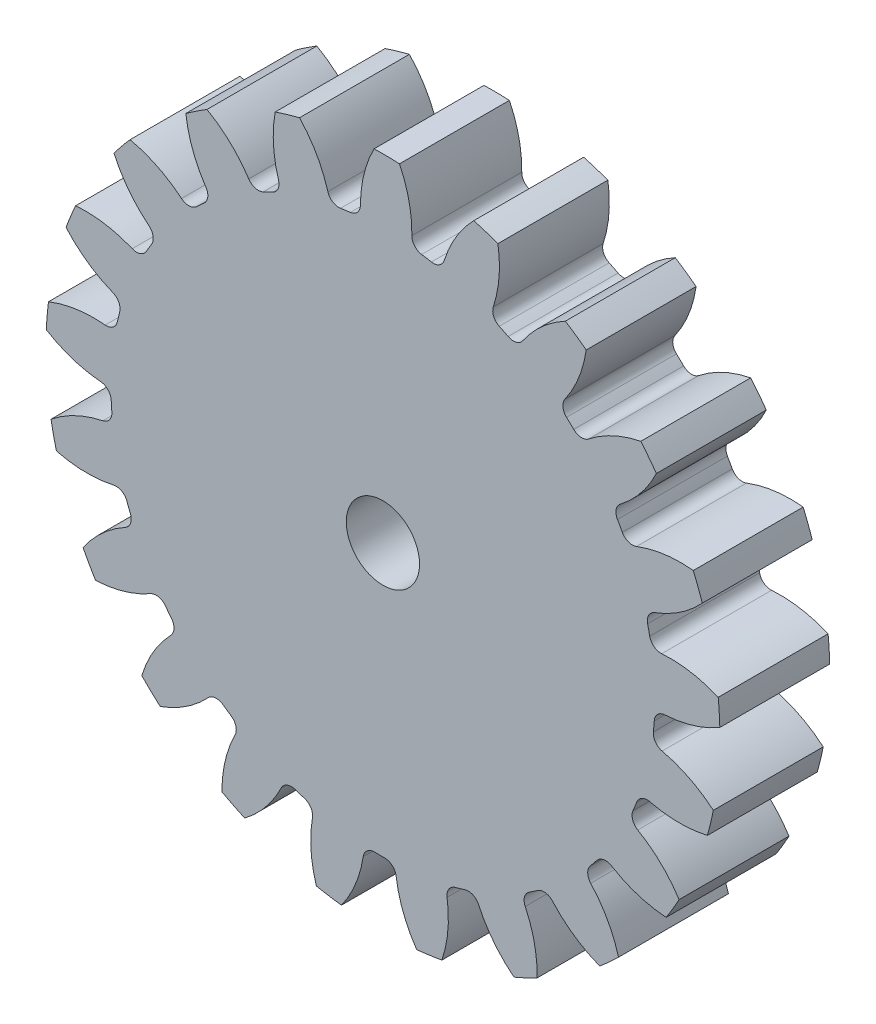
SolidWorks part; units mm, degrees
ref_plane "Front" through (0, 0, 0) normal (0, 0, 1) x (1, 0, 0)
ref_plane "Top" through (0, 0, 0) normal (0, 1, 0) x (1, 0, 0)
ref_plane "Right" through (0, 0, 0) normal (1, 0, 0) x (0, 0, -1)
sketch "Sketch3" plane through (0, 0, 0) normal (0, 0, 1) x (1, 0, 0)
  circle A0 centre (0, 0) radius 29.21
  dimension "od" = 58.42
extrude "gearBody" add sketch "Sketch3" along normal blind 9.525
sketch "Sketch2" plane through (0, 0, 0) normal (0, 0, 1) x (1, 0, 0)
  line L0 (0, 0) -> (23.855, 9.8811) construction
  line L1 (31.4408, -9.4565) -> (0, 0) construction
  line L2 (0, 0) -> (36.3143, 0) construction
  line L3 (26.6681, -0.3206) -> (26.3271, -4.2627) construction
  line L5 (26.4976, -2.2916) -> (0, 0) construction
  line L7 (0, 0) -> (25.8205, 0) construction
  arc A0 (25.8153, -0.5182) -> (25.521, -3.9216) centre (0, 0) ccw construction
  arc A1 (29.2004, 0.7479) -> (28.6384, -5.7501) centre (0, 0) ccw construction
  arc A2 (26.6681, -0.3206) -> (26.3271, -4.2627) centre (0, 0) ccw construction
  arc A3 (23.4425, -2.4594) -> (23.5167, -1.6019) centre (0, 0) ccw
  arc A4 (31.4408, -9.4565) -> (24.1996, -3.5222) centre (21.8044, -13.8299) ccw
  arc A5 (31.4408, -9.4565) -> (32.5975, 3.9182) centre (0, 0) ccw
  arc A6 (32.5975, 3.9182) -> (24.445, -0.6849) centre (23.855, 9.8811) cw
  arc A7 (23.5167, -1.6019) -> (24.445, -0.6849) centre (24.4999, -1.6689) cw
  arc A8 (24.1996, -3.5222) -> (23.4425, -2.4594) centre (24.4227, -2.5622) cw
  point P6 (32.5975, 3.9182)
  point P22 (31.4408, -9.4565)
  dimension "baseDia" = 51.641
  dimension "od" = 58.42
  dimension "pd" = 53.34
  dimension "rd" = 47.1424
  dimension "rFillet" = 0.9855
  dimension "pointX" = 32.5975
  dimension "pointY" = 3.9182
  dimension "CTT" = 3.9421
  dimension "flankCenterAngle" = 22.5
extrude "toothCut" cut sketch "Sketch2" along normal through all
pattern_circular "CirPattern1" count 21 over 360 about axis through (0, 0, 0) along (0, 0, 1) of "toothCut"
sketch "hub1Dia" plane through (0, 0, 0) normal (0, 0, -1) x (-1, 0, 0)
  circle A0 centre (0, 0) radius 12.7
  dimension "hub1Dia" = 25.4
sketch "hub2Dia" plane through (0, 0, 9.525) normal (0, 0, 1) x (1, 0, 0)
  circle A0 centre (0, 0) radius 12.7
  dimension "hub2dia" = 25.4
sketch "boreDia" plane through (0, 0, 0) normal (0, 0, 1) x (1, 0, 0)
  circle A0 centre (0, 0) radius 3.175
  dimension "boreDia" = 6.35
extrude "bore" cut sketch "boreDia" against normal mid plane 25400
